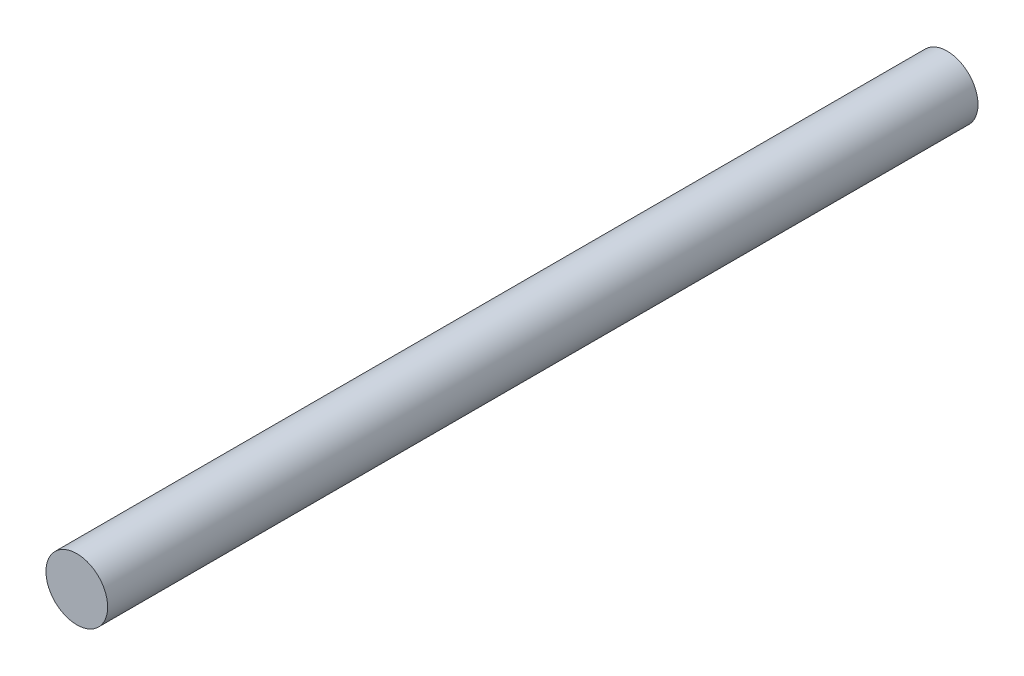
SolidWorks part; units mm, degrees
ref_plane "Přední rovina" through (0, 0, 0) normal (0, 0, 1) x (1, 0, 0)
ref_plane "Horní rovina" through (0, 0, 0) normal (0, 1, 0) x (1, 0, 0)
ref_plane "Pravá rovina" through (0, 0, 0) normal (1, 0, 0) x (0, 0, -1)
sketch "Skica1" plane through (0, 0, 0) normal (0, 0, 1) x (1, 0, 0)
  circle A0 centre (0, 0) radius 1
  dimension "D1" = 2
extrude "Přidat vysunutím1" add sketch "Skica1" along normal blind 28.2
